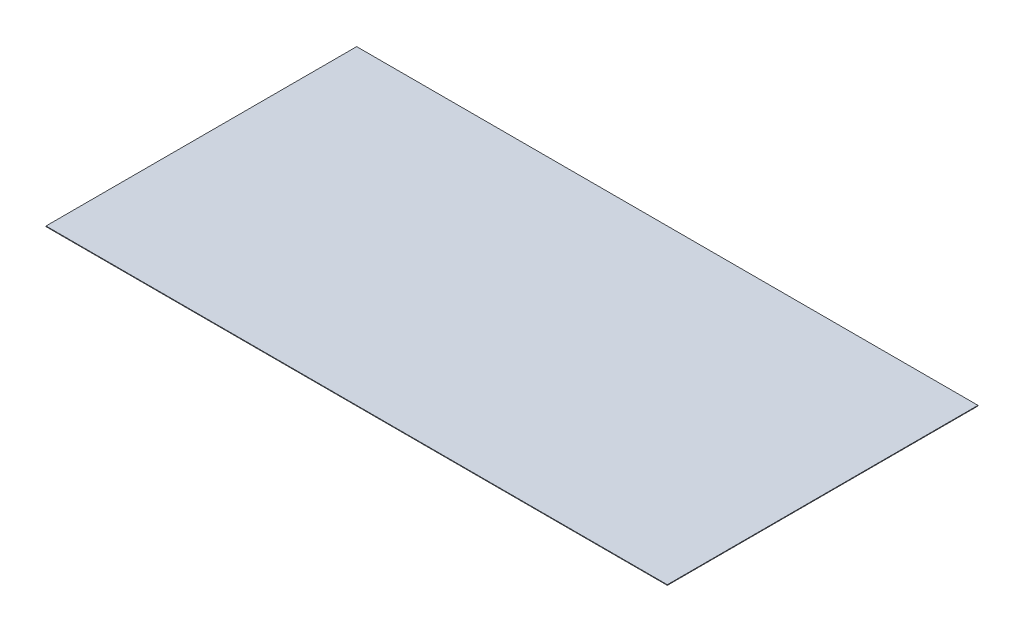
SolidWorks part; units mm, degrees
material "6061-T6 (SS)"
ref_plane "Front Plane" through (0, 0, 0) normal (0, 0, 1) x (1, 0, 0)
ref_plane "Top Plane" through (0, 0, 0) normal (0, 1, 0) x (1, 0, 0)
ref_plane "Right Plane" through (0, 0, 0) normal (1, 0, 0) x (0, 0, -1)
sketch "Sketch1" plane through (0, 0, 0) normal (0, 1, 0) x (1, 0, 0)
  line L1 (3350, -1675) -> (-3350, -1675)
  line L2 (3350, -1675) -> (3350, 1675)
  line L3 (3350, 1675) -> (-3350, 1675)
  line L4 (-3350, -1675) -> (-3350, 1675)
  line L5 (3350, -1675) -> (-3350, 1675) construction
  line L6 (3350, 1675) -> (-3350, -1675) construction
  point P0 (0, 0)
  dimension "D1" = 6700
  dimension "D2" = 3350
extrude "Boss-Extrude1" add sketch "Sketch1" along normal blind 6.35
